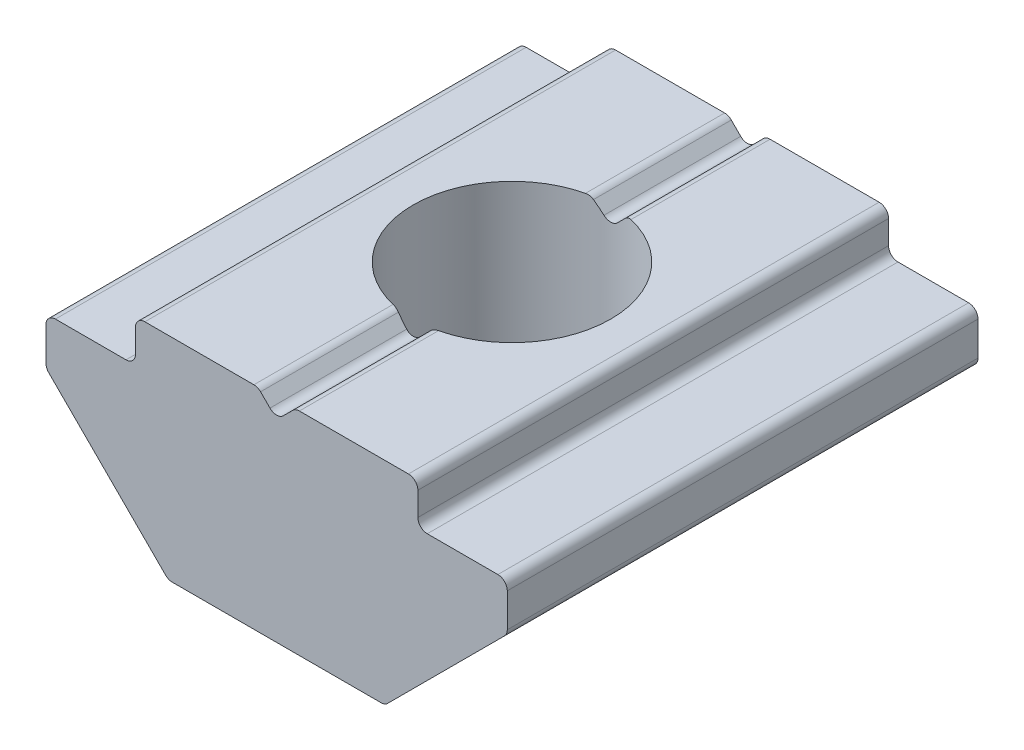
SolidWorks part; units mm, degrees
ref_plane "Front Plane" through (0, 0, 0) normal (0, 0, 1) x (1, 0, 0)
ref_plane "Top Plane" through (0, 0, 0) normal (0, 1, 0) x (1, 0, 0)
ref_plane "Right Plane" through (0, 0, 0) normal (1, 0, 0) x (0, 0, -1)
ref_plane "Plane1" through (0, 0, 5) normal (0, 0, 1) x (1, 0, 0)
sketch "Sketch1" plane through (0, 0, 5) normal (0, 0, 1) x (1, 0, 0)
  line L0 (4.9, -1) -> (4.9, 0.9)
  line L1 (4.9, 0.9) -> (-4.9, 0.9)
  line L2 (-4.9, 0.9) -> (-4.9, -1)
  line L3 (-4.9, -1) -> (-2.3, -3.6)
  line L4 (-2.3, -3.6) -> (2.3, -3.6)
  line L5 (2.3, -3.6) -> (4.9, -1)
extrude "Boss-Extrude1" add sketch "Sketch1" against normal blind 10
sketch "Sketch2" plane through (0, 0, -5) normal (0, 0, -1) x (-1, 0, 0)
  line L0 (4.9, 0.9) -> (3, 0.9)
  line L1 (3, 0.9) -> (3, 0)
  line L2 (3, 0) -> (4.9, 0)
  line L3 (4.9, 0) -> (4.9, 0.9)
extrude "Cut-Extrude1" cut sketch "Sketch2" against normal through all
sketch "Sketch3" plane through (0, 0, -5) normal (0, 0, -1) x (-1, 0, 0)
  line L0 (-4.9, 0) -> (-3, 0)
  line L1 (-3, 0) -> (-3, 0.9)
  line L2 (-3, 0.9) -> (-4.9, 0.9)
  line L3 (-4.9, 0.9) -> (-4.9, 0)
extrude "Cut-Extrude2" cut sketch "Sketch3" against normal through all
sketch "Sketch4" plane through (0, 0, -5) normal (0, 0, -1) x (-1, 0, 0)
  line L0 (0.4, 0.9) -> (-0.4, 0.9)
  line L1 (-0.4, 0.9) -> (0, 0.5)
  line L2 (0, 0.5) -> (0.4, 0.9)
extrude "Cut-Extrude3" cut sketch "Sketch4" against normal through all
hole_wizard "Ø4.2 (4.2) Diameter Hole1" positions "Sketch6" profile "Sketch5" hole size "Ø4.2" standard "ANSI Metric"
sketch "Sketch6" plane through (0, -3.6, 0) normal (0, -1, 0) x (-1, 0, 0)
  point P0 (0, 0)
sketch "Sketch5" plane through (0, -3.6, 0) normal (1, 0, 0) x (0, 0, -1)
  line L0 (0, 0) -> (0, 4.5)
  line L1 (0, 4.5) -> (2.1, 4.5)
  line L2 (2.1, 4.5) -> (2.1, 0)
  line L5 (2.1, 0) -> (0, 0)
  line L11 (0, -6.35) -> (0, 107.95) construction
  dimension "Thru Hole Dia." = 4.2
  dimension "Thru Hole Depth" = 4.5
fillet "Fillet1" radius 0.2 16 edges at (4.9, 0, 0) (3, 0, 0) (-4.9, -1, 0) (3, 0.9, 0) (-3, 0, 0) (0.4, 0.9, -3.5308) (0, 0.5, 3.55) (-0.4, 0.9, -3.5308) (4.9, -1, 0) (-3, 0.9, 0) (0, 0.5, -3.55) (-0.4, 0.9, 3.5308) (-4.9, 0, 0) (-2.3, -3.6, 0) (0.4, 0.9, 3.5308) (2.3, -3.6, 0)
